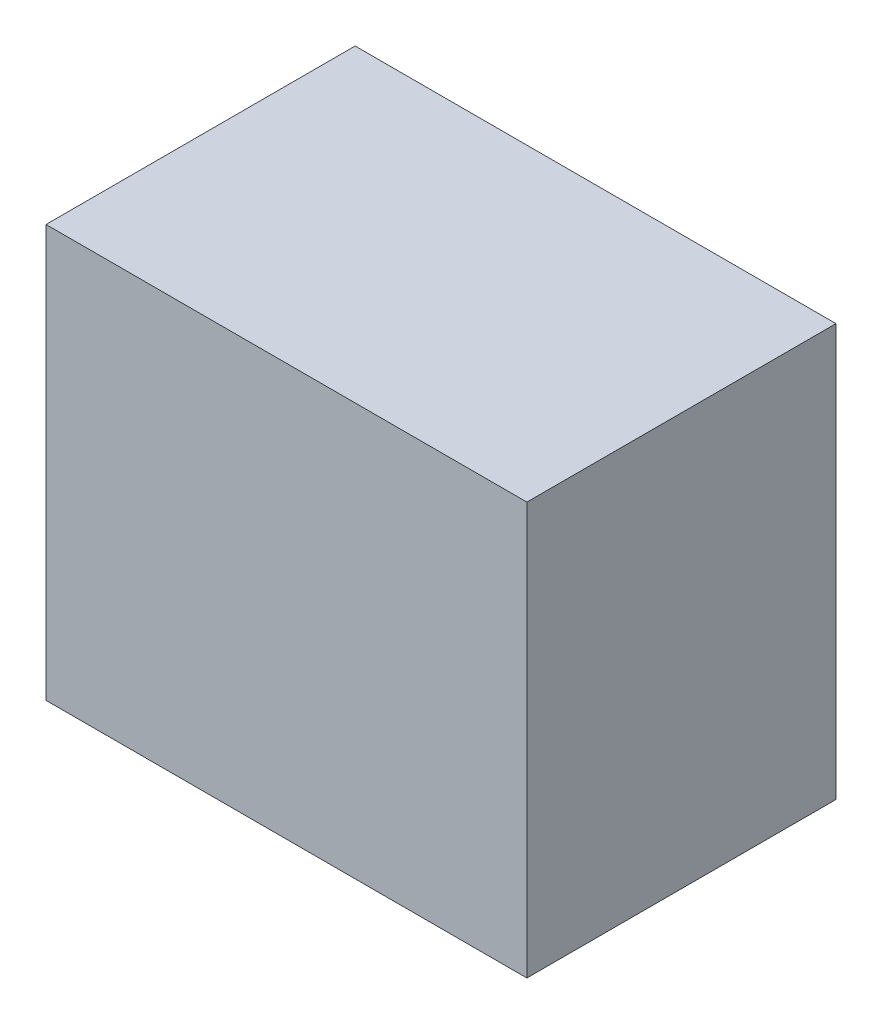
SolidWorks part; units mm, degrees
ref_plane "Front Plane" through (0, 0, 0) normal (0, 0, 1) x (1, 0, 0)
ref_plane "Top Plane" through (0, 0, 0) normal (0, 1, 0) x (1, 0, 0)
ref_plane "Right Plane" through (0, 0, 0) normal (1, 0, 0) x (0, 0, -1)
sketch "Sketch1" plane through (0, 0, 0) normal (0, 1, 0) x (1, 0, 0)
  line L1 (-22.225, -14.2875) -> (22.225, -14.2875)
  line L2 (-22.225, -14.2875) -> (-22.225, 14.2875)
  line L3 (-22.225, 14.2875) -> (22.225, 14.2875)
  line L4 (22.225, -14.2875) -> (22.225, 14.2875)
  line L5 (-22.225, -14.2875) -> (22.225, 14.2875) construction
  line L6 (-22.225, 14.2875) -> (22.225, -14.2875) construction
  point P0 (0, 0)
  dimension "D1" = 44.45
  dimension "D2" = 28.575
extrude "Boss-Extrude1" add sketch "Sketch1" along normal blind 38.1
